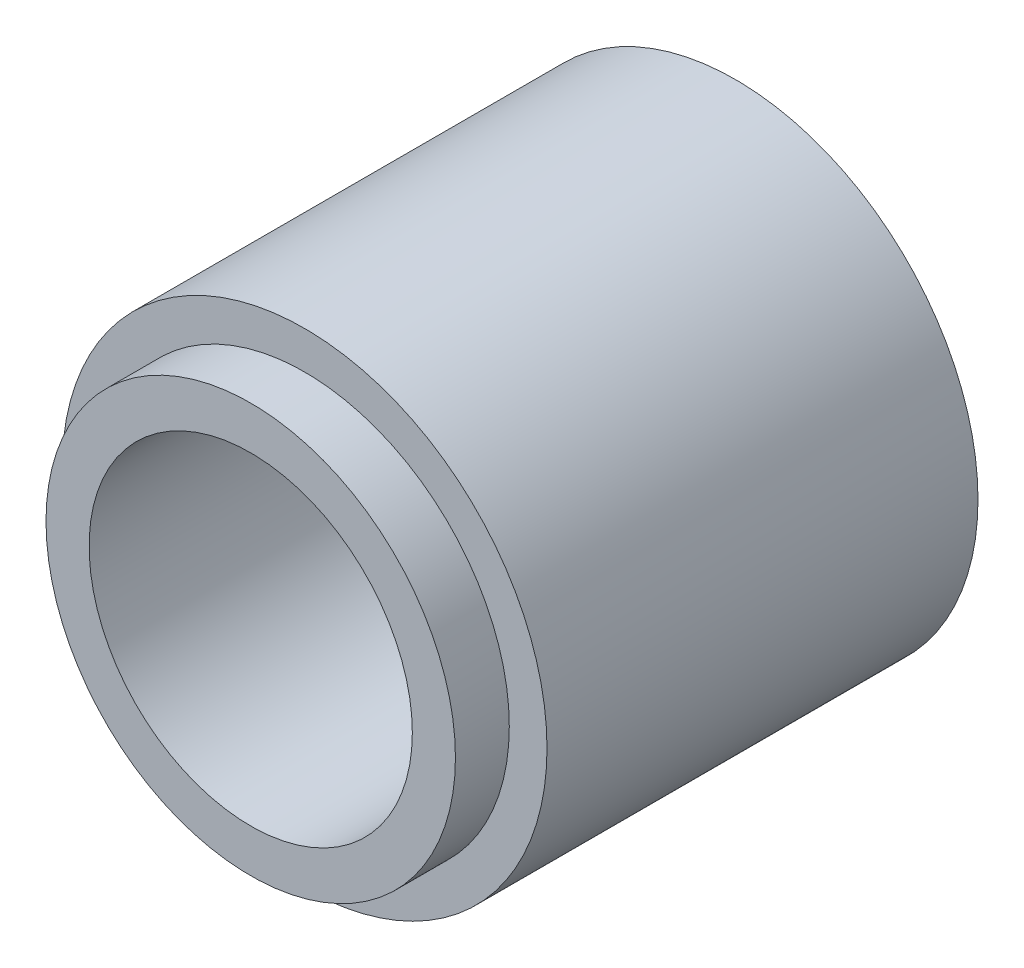
SolidWorks part; units mm, degrees
material "黄铜"
ref_plane "前视基准面" through (0, 0, 0) normal (0, 0, 1) x (1, 0, 0)
ref_plane "上视基准面" through (0, 0, 0) normal (0, 1, 0) x (1, 0, 0)
ref_plane "右视基准面" through (0, 0, 0) normal (1, 0, 0) x (0, 0, -1)
other "Configuration Table"
sketch "草图1" plane through (0, 0, 0) normal (0, 0, 1) x (1, 0, 0)
  circle A0 centre (0, 0) radius 1.5
  circle A1 centre (0, 0) radius 2.25
  dimension "D1" = 3
  dimension "D2" = 4.5
extrude "凸台-拉伸1" add sketch "草图1" along normal blind 4.5
sketch "草图2" plane through (0, 0, 4.5) normal (0, 0, 1) x (1, 0, 0)
  circle A0 centre (0, 0) radius 1.9
  circle A1 centre (0, 0) radius 2.25
  dimension "D1" = 4.5
  dimension "D2" = 3.8
extrude "切除-拉伸1" cut sketch "草图2" against normal blind 0.5
